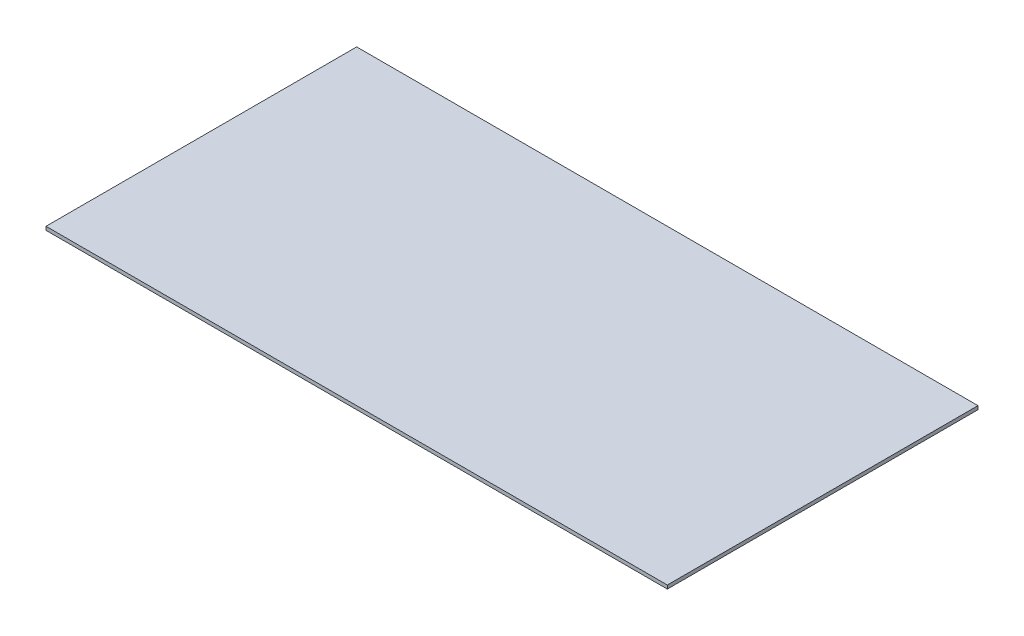
SolidWorks part; units mm, degrees
ref_plane "Front" through (0, 0, 0) normal (0, 0, 1) x (1, 0, 0)
ref_plane "Top" through (0, 0, 0) normal (0, 1, 0) x (1, 0, 0)
ref_plane "Right" through (0, 0, 0) normal (1, 0, 0) x (0, 0, -1)
sketch "Эскиз1" plane through (0, 0, 0) normal (0, 1, 0) x (1, 0, 0)
  line L1 (-140, 70) -> (140, 70)
  line L2 (-140, 70) -> (-140, -70)
  line L3 (-140, -70) -> (140, -70)
  line L4 (140, 70) -> (140, -70)
  line L5 (-140, 70) -> (140, -70) construction
  line L6 (-140, -70) -> (140, 70) construction
  point P0 (0, 0)
  dimension "D1" = 280
  dimension "D2" = 140
extrude "Бобышка-Вытянуть1" add sketch "Эскиз1" along normal blind 1.6
